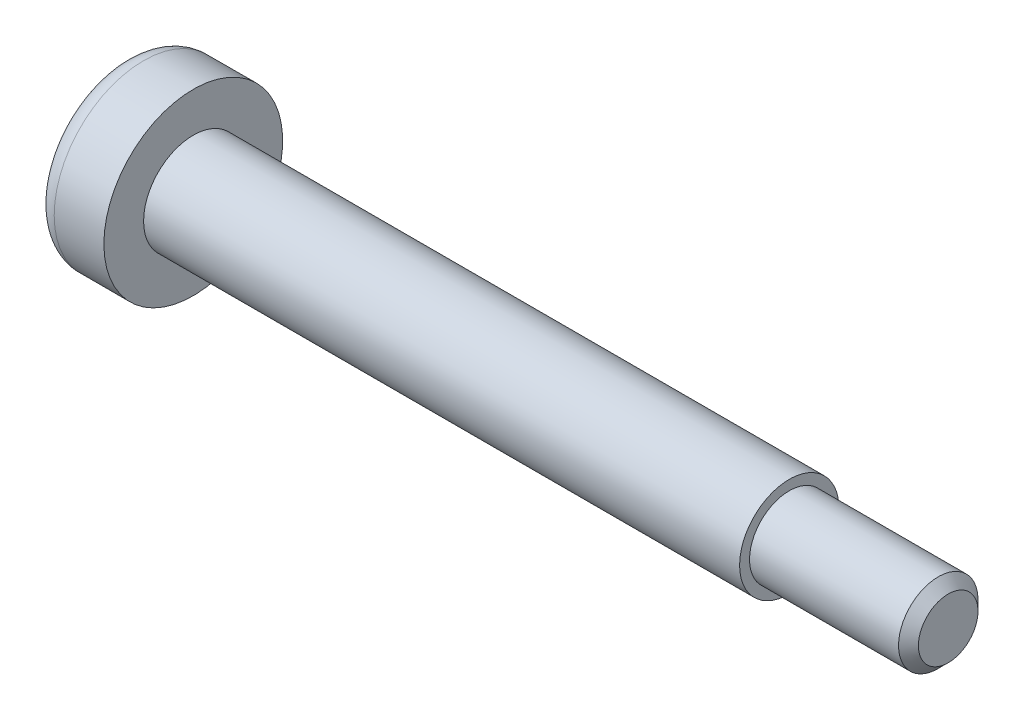
SolidWorks part; units mm, degrees
material "不锈钢 (铁素体)"
ref_plane "前视基准面" through (0, 0, 0) normal (0, 0, 1) x (1, 0, 0)
ref_plane "上视基准面" through (0, 0, 0) normal (0, 1, 0) x (1, 0, 0)
ref_plane "右视基准面" through (0, 0, 0) normal (1, 0, 0) x (0, 0, -1)
sketch "草图1" plane through (0, 0, 0) normal (0, 0, 1) x (1, 0, 0)
  line L0 (0, 0) -> (41.5, 0) construction
  line L1 (0, 0) -> (0, 4.5)
  line L2 (0, 4.5) -> (3.5, 4.5)
  line L3 (3.5, 4.5) -> (3.5, 2.5)
  line L4 (3.5, 2.5) -> (33.5, 2.5)
  line L5 (33.5, 2.5) -> (33.5, 2)
  line L6 (33.5, 2) -> (41.5, 2)
  line L7 (41.5, 2) -> (41.5, 0)
  line L8 (0, 0) -> (41.5, 0)
  dimension "D1" = 9
  dimension "D2" = 5
  dimension "D3" = 4
  dimension "D4" = 8
  dimension "D5" = 3.5
  dimension "D6" = 30
revolve "旋转1" add sketch "草图1" angle 360 about L0
cosmetic thread "装饰螺纹线1" parameters "D2"=3.242
sketch "草图2" plane through (0, 0, 0) normal (-1, 0, 0) x (0, 0, 1)
  line L0 (0, 0) -> (0, 1.7321) construction
  line L1 (0, 1.7321) -> (-1.5, 0.866)
  line L2 (-1.5, 0.866) -> (-1.5, -0.866)
  line L3 (-1.5, -0.866) -> (0, -1.7321)
  line L4 (0, -1.7321) -> (1.5, -0.866)
  line L5 (1.5, -0.866) -> (1.5, 0.866)
  line L6 (1.5, 0.866) -> (0, 1.7321)
  circle A0 centre (0, 0) radius 1.5 construction
  dimension "D1" = 3
extrude "切除-拉伸1" cut sketch "草图2" against normal blind 2.4
fillet "圆角1" radius 1 1 edges at (0, 0, 4.5)
chamfer "倒角1" distance 0.5 angle 45 1 edges at (41.5, 0, 2)
